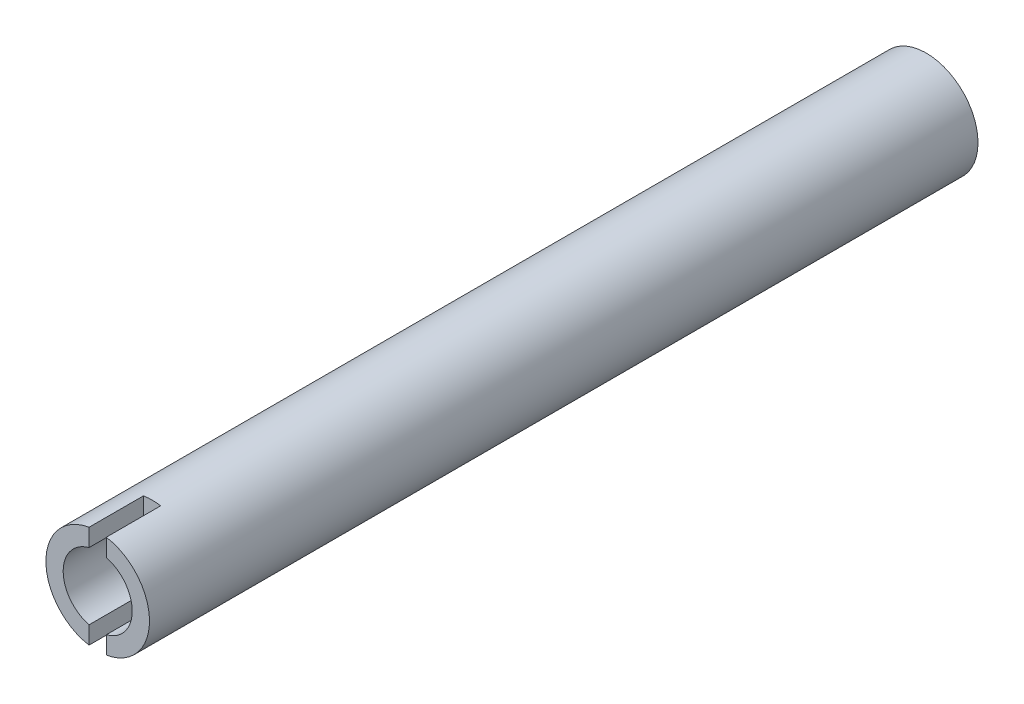
SolidWorks part; units mm, degrees
material "6061-T6 (SS)"
ref_plane "Front" through (0, 0, 0) normal (0, 0, 1) x (1, 0, 0)
ref_plane "Top" through (0, 0, 0) normal (0, 1, 0) x (1, 0, 0)
ref_plane "Right" through (0, 0, 0) normal (1, 0, 0) x (0, 0, -1)
sketch "Sketch1" plane through (0, 0, 0) normal (0, 0, 1) x (1, 0, 0)
  circle A0 centre (0, 0) radius 9.525
  circle A1 centre (0, 0) radius 6.35
  dimension "D1" = 19.05
  dimension "D2" = 12.7
extrude "Boss-Extrude1" add sketch "Sketch1" along normal blind 152.4
sketch "Sketch2" plane through (0, 0, 152.4) normal (0, 0, 1) x (1, 0, 0)
  line L1 (-1.5875, 12.5895) -> (1.5875, 12.5895)
  line L2 (-1.5875, 12.5895) -> (-1.5875, -12.5895)
  line L3 (-1.5875, -12.5895) -> (1.5875, -12.5895)
  line L4 (1.5875, 12.5895) -> (1.5875, -12.5895)
  line L5 (-1.5875, 12.5895) -> (1.5875, -12.5895) construction
  line L6 (-1.5875, -12.5895) -> (1.5875, 12.5895) construction
  point P0 (0, 0)
  dimension "D1" = 3.175
extrude "Cut-Extrude1" cut sketch "Sketch2" against normal blind 10
sketch "Sketch3" plane through (0, 0, 0) normal (1, 0, 0) x (0, 0, -1)
  circle A0 centre (-8.89, 0) radius 3.2639
  dimension "D2" = 6.5278
  dimension "D1" = 8.89
extrude "Cut-Extrude2" [suppressed] cut sketch "Sketch3" against normal mid plane 50
